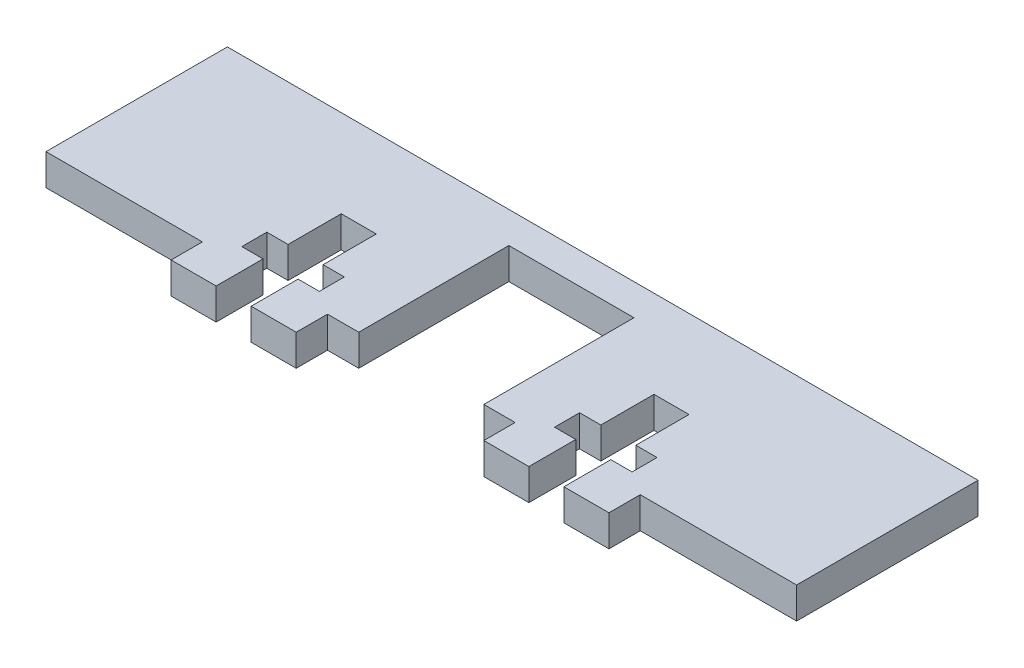
SolidWorks part; units mm, degrees
ref_plane "Front Plane" through (0, 0, 0) normal (0, 0, 1) x (1, 0, 0)
ref_plane "Top Plane" through (0, 0, 0) normal (0, 1, 0) x (1, 0, 0)
ref_plane "Right Plane" through (0, 0, 0) normal (1, 0, 0) x (0, 0, -1)
sketch "Sketch1" plane through (0, 0, 0) normal (0, 1, 0) x (1, 0, 0)
  line L0 (0, 0) -> (0, 35.7797) construction
  line L1 (-9.525, -18.415) -> (-9.525, -15.24)
  line L2 (-15.875, -18.415) -> (-15.875, -5.715) construction
  line L3 (-9.525, -18.415) -> (-14.097, -18.415)
  line L4 (-22.225, -18.415) -> (-22.225, -15.24)
  line L5 (-38.1, -15.24) -> (-22.225, -15.24)
  line L6 (-38.1, -15.24) -> (-38.1, 3.175)
  line L7 (-38.1, 3.175) -> (38.1, 3.175)
  line L8 (-9.525, -15.24) -> (-6.35, -15.24)
  line L9 (-6.35, -15.24) -> (-6.35, 0)
  line L10 (6.35, 0) -> (-6.35, 0)
  line L11 (-17.653, -18.415) -> (-17.653, -13.6525)
  line L12 (-17.653, -13.6525) -> (-19.812, -13.6525)
  line L13 (-19.812, -13.6525) -> (-19.812, -11.1125)
  line L14 (-19.812, -11.1125) -> (-17.653, -11.1125)
  line L15 (-17.653, -11.1125) -> (-17.653, -5.715)
  line L16 (-17.653, -5.715) -> (-14.097, -5.715)
  line L17 (-14.097, -11.1125) -> (-14.097, -5.715)
  line L18 (-11.938, -11.1125) -> (-14.097, -11.1125)
  line L19 (-11.938, -13.6525) -> (-11.938, -11.1125)
  line L20 (-14.097, -13.6525) -> (-11.938, -13.6525)
  line L21 (-14.097, -18.415) -> (-14.097, -13.6525)
  line L22 (-17.653, -18.415) -> (-22.225, -18.415)
  line L23 (17.653, -18.415) -> (22.225, -18.415)
  line L24 (14.097, -18.415) -> (14.097, -13.6525)
  line L25 (14.097, -13.6525) -> (11.938, -13.6525)
  line L26 (11.938, -13.6525) -> (11.938, -11.1125)
  line L27 (11.938, -11.1125) -> (14.097, -11.1125)
  line L28 (14.097, -11.1125) -> (14.097, -5.715)
  line L29 (17.653, -5.715) -> (14.097, -5.715)
  line L30 (17.653, -11.1125) -> (17.653, -5.715)
  line L31 (19.812, -11.1125) -> (17.653, -11.1125)
  line L32 (19.812, -13.6525) -> (19.812, -11.1125)
  line L33 (17.653, -13.6525) -> (19.812, -13.6525)
  line L34 (17.653, -18.415) -> (17.653, -13.6525)
  line L35 (6.35, -15.24) -> (6.35, 0)
  line L36 (9.525, -15.24) -> (6.35, -15.24)
  line L37 (38.1, -15.24) -> (38.1, 3.175)
  line L38 (38.1, -15.24) -> (22.225, -15.24)
  line L39 (22.225, -18.415) -> (22.225, -15.24)
  line L40 (9.525, -18.415) -> (14.097, -18.415)
  line L41 (9.525, -18.415) -> (9.525, -15.24)
  point P43 (0, 3.175)
  dimension "D1" = 12.7
  dimension "D2" = 9.525
  dimension "D3" = 6.35
  dimension "D4" = 15.24
  dimension "D5" = 3.175
  dimension "D6" = 3.175
  dimension "D7" = 38.1
  dimension "D8" = 12.7
  dimension "D9" = 3.937
  dimension "D10" = 1.778
  dimension "D11" = 4.7625
  dimension "D12" = 2.54
extrude "Boss-Extrude1" add sketch "Sketch1" along normal blind 3.175
